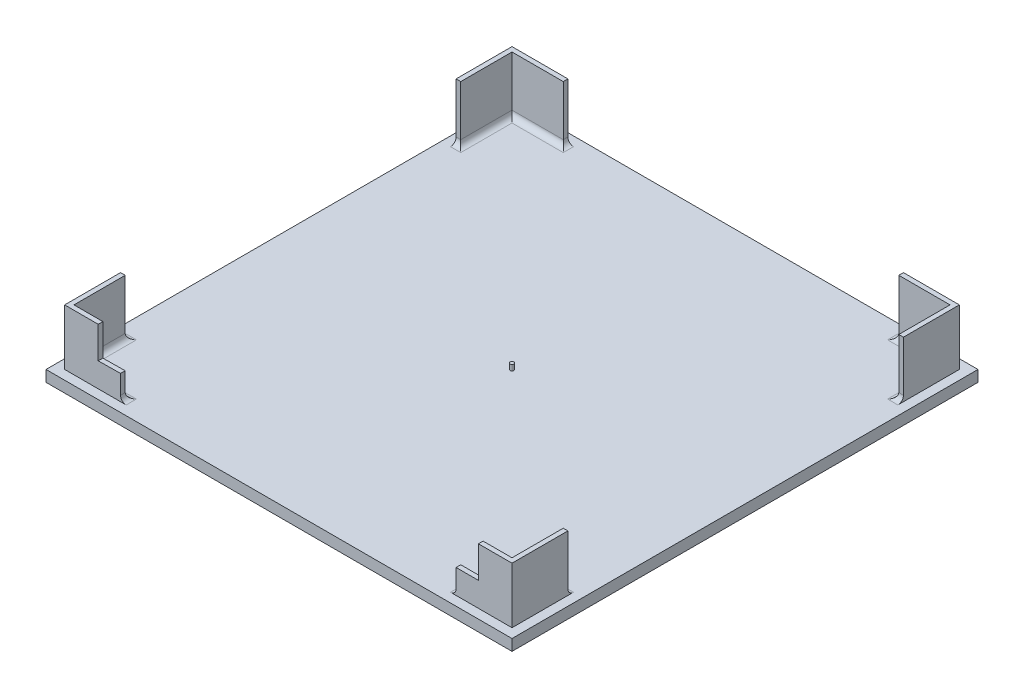
SolidWorks part; units mm, degrees
material "ABS"
ref_plane "Alzado" through (0, 0, 0) normal (0, 0, 1) x (1, 0, 0)
ref_plane "Planta" through (0, 0, 0) normal (0, 1, 0) x (1, 0, 0)
ref_plane "Vista lateral" through (0, 0, 0) normal (1, 0, 0) x (0, 0, -1)
sketch "Croquis1" plane through (0, 0, 0) normal (0, 1, 0) x (1, 0, 0)
  line L1 (-125, 125) -> (125, 125)
  line L2 (-125, 125) -> (-125, -125)
  line L3 (-125, -125) -> (125, -125)
  line L4 (125, 125) -> (125, -125)
  point P0 (0, 0)
  dimension "D1" = 250
  dimension "D2" = 250
extrude "Saliente-Extruir1" add sketch "Croquis1" along normal blind 6
sketch "Croquis2" plane through (0, 6, 0) normal (0, 1, 0) x (1, 0, 0)
  line L0 (-120, 120) -> (-120, 90)
  line L1 (-120, 90) -> (-117.5, 90)
  line L2 (-117.5, 90) -> (-117.5, 117.5)
  line L3 (-117.5, 117.5) -> (-90, 117.5)
  line L4 (-90, 117.5) -> (-90, 120)
  line L5 (-90, 120) -> (-120, 120)
  line L6 (125, 125) -> (-125, 125) construction
  line L7 (-125, 125) -> (-125, -125) construction
  line L8 (120, 120) -> (90, 120)
  line L9 (90, 120) -> (90, 117.5)
  line L10 (90, 117.5) -> (117.5, 117.5)
  line L11 (117.5, 117.5) -> (117.5, 90)
  line L12 (117.5, 90) -> (120, 90)
  line L13 (120, 90) -> (120, 120)
  line L14 (120, -120) -> (120, -90)
  line L15 (120, -90) -> (117.5, -90)
  line L16 (117.5, -90) -> (117.5, -117.5)
  line L17 (117.5, -117.5) -> (90, -117.5)
  line L18 (90, -117.5) -> (90, -120)
  line L19 (90, -120) -> (120, -120)
  line L20 (-120, -120) -> (-120, -90)
  line L21 (-120, -90) -> (-117.5, -90)
  line L22 (-117.5, -90) -> (-117.5, -117.5)
  line L23 (-117.5, -117.5) -> (-90, -117.5)
  line L24 (-90, -117.5) -> (-90, -120)
  line L25 (-90, -120) -> (-120, -120)
  line L26 (125, -125) -> (125, 125) construction
  line L27 (-125, -125) -> (125, -125) construction
  dimension "D1" = 5
  dimension "D2" = 5
  dimension "D3" = 2.5
  dimension "D4" = 2.5
  dimension "D5" = 30
  dimension "D6" = 5
  dimension "D7" = 5
  dimension "D8" = 5
  dimension "D9" = 5
  dimension "D10" = 5
  dimension "D11" = 5
extrude "Saliente-Extruir2" add sketch "Croquis2" along normal blind 30
fillet "Redondeo1" radius 3 16 edges at (90, 6, 118.75) (103.75, 6, 117.5) (117.5, 6, 103.75) (118.75, 6, 90) (-90, 6, 118.75) (-103.75, 6, 117.5) (-118.75, 6, 90) (-117.5, 6, 103.75) (90, 6, -118.75) (103.75, 6, -117.5) (117.5, 6, -103.75) (118.75, 6, -90) (-90, 6, -118.75) (-118.75, 6, -90) (-103.75, 6, -117.5) (-117.5, 6, -103.75)
sketch "Croquis3" plane through (0, 0, 120) normal (0, 0, 1) x (1, 0, 0)
  line L0 (-102, 36) -> (-102, 19)
  line L1 (-120, 36) -> (-90, 36) construction
  line L2 (-102, 19) -> (-90, 19.1539)
  line L3 (-90, 36) -> (-90, 9) construction
  line L4 (-90, 19.1539) -> (-90, 36)
  line L5 (-90, 36) -> (-102, 36)
  line L6 (90, 36) -> (102, 36)
  line L7 (90, 36) -> (120, 36) construction
  line L8 (102, 36) -> (102, 19)
  line L9 (102, 19) -> (90, 19)
  line L10 (90, 36) -> (90, 9) construction
  line L11 (90, 19) -> (90, 36)
  dimension "D1" = 12
  dimension "D2" = 12
  dimension "D3" = 17
  dimension "D4" = 17
  dimension "D5" = 12
extrude "Cortar-Extruir1" cut sketch "Croquis3" against normal up to next
sketch "Croquis4" plane through (0, 6, 0) normal (0, 1, 0) x (1, 0, 0)
  circle A0 centre (0, 0) radius 1
  dimension "D1" = 2
extrude "Saliente-Extruir3" add sketch "Croquis4" along normal blind 3
